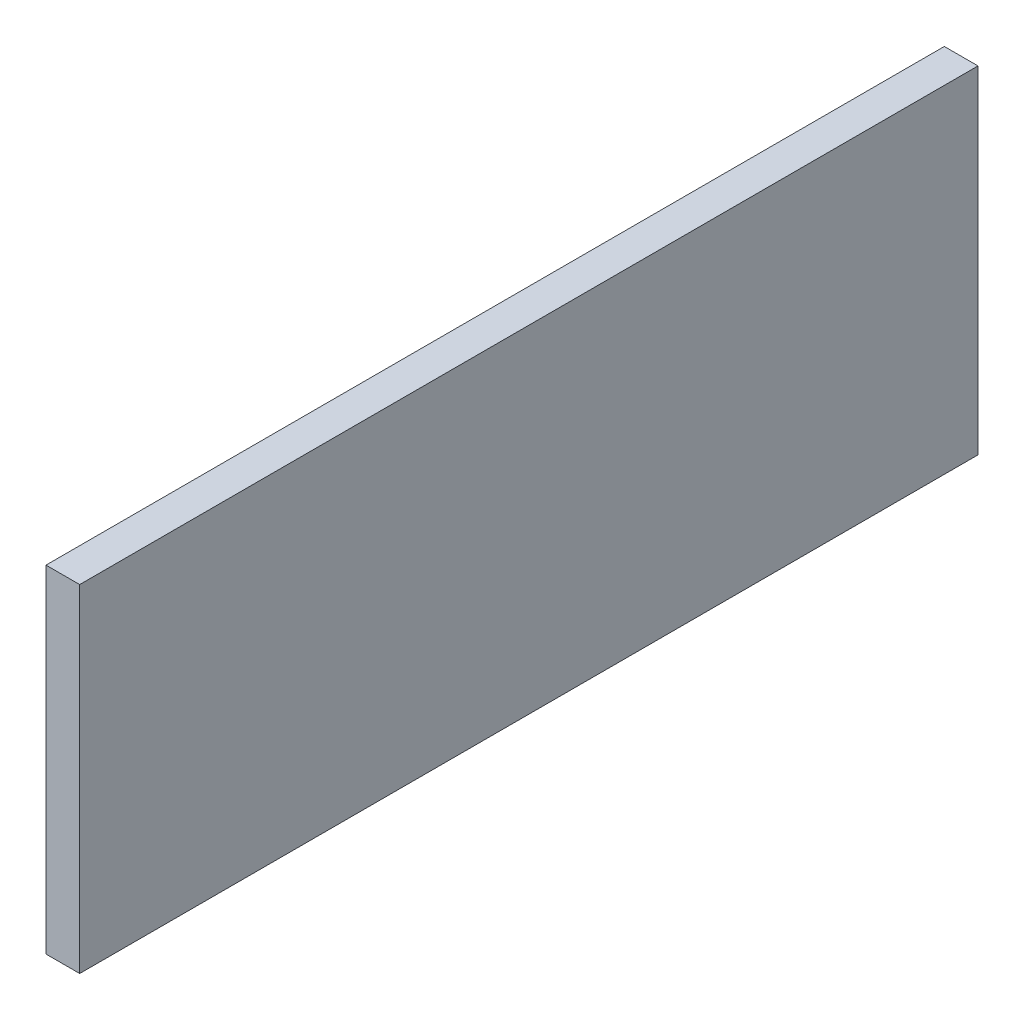
SolidWorks part; units mm, degrees
ref_plane "Front" through (0, 0, 0) normal (0, 0, 1) x (1, 0, 0)
ref_plane "Top" through (0, 0, 0) normal (0, 1, 0) x (1, 0, 0)
ref_plane "Right" through (0, 0, 0) normal (1, 0, 0) x (0, 0, -1)
sketch "Sketch1" plane through (0, 0, 0) normal (1, 0, 0) x (0, 0, -1)
  line L1 (-34.1985, 33.88) -> (45.8015, 33.88)
  line L2 (-34.1985, 33.88) -> (-34.1985, 3.88)
  line L3 (-34.1985, 3.88) -> (45.8015, 3.88)
  line L4 (45.8015, 33.88) -> (45.8015, 3.88)
  dimension "D1" = 80
  dimension "D2" = 30
extrude "Boss-Extrude1" add sketch "Sketch1" along normal blind 3
